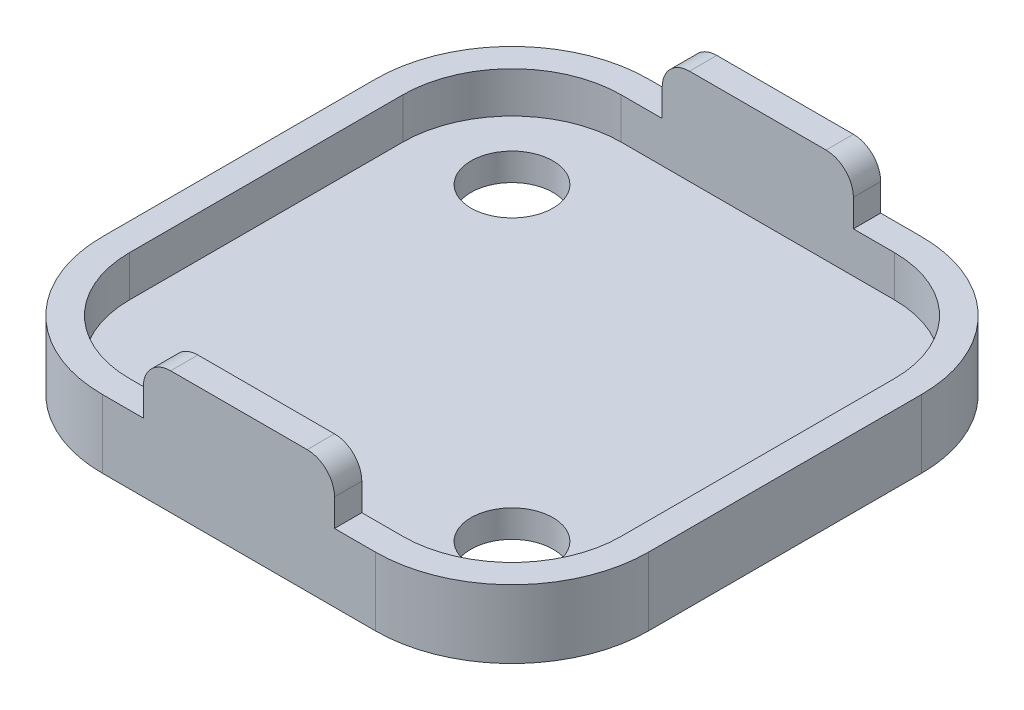
SolidWorks part; units mm, degrees
ref_plane "Front Plane" through (0, 0, 0) normal (0, 0, 1) x (1, 0, 0)
ref_plane "Top Plane" through (0, 0, 0) normal (0, 1, 0) x (1, 0, 0)
ref_plane "Right Plane" through (0, 0, 0) normal (1, 0, 0) x (0, 0, -1)
sketch "Sketch1" plane through (0, 0, 0) normal (0, 1, 0) x (1, 0, 0)
  line L1 (-10, -10) -> (10, -10)
  line L2 (-10, -10) -> (-10, 10)
  line L3 (-10, 10) -> (10, 10)
  line L4 (10, -10) -> (10, 10)
  line L5 (-10, -10) -> (10, 10) construction
  line L6 (-10, 10) -> (10, -10) construction
  point P0 (0, 0)
  dimension "D1" = 20
extrude "Boss-Extrude1" add sketch "Sketch1" along normal blind 2.5
fillet "Fillet1" radius 5 4 edges at (-10, 1.25, -10) (-10, 1.25, 10) (10, 1.25, -10) (10, 1.25, 10)
sketch "Sketch2" plane through (0, 2.5, 0) normal (0, 1, 0) x (1, 0, 0)
  circle A0 centre (-5.6569, 5.6569) radius 1.35 construction
  circle A1 centre (-5.6569, 5.6569) radius 1.35 construction
  circle A2 centre (5.6569, -5.6569) radius 1.35 construction
  circle A3 centre (5.6569, -5.6569) radius 1.35 construction
  circle A4 centre (5.6569, -5.6569) radius 1.5
  circle A5 centre (-5.6569, 5.6569) radius 1.5
  dimension "D1" = 3
extrude "Cut-Extrude1" cut sketch "Sketch2" against normal blind 10
sketch "Sketch3" plane through (0, 2.5, 0) normal (0, 1, 0) x (1, 0, 0)
  line L8 (5, 9) -> (-5, 9)
  line L9 (-9, 5) -> (-9, -5)
  line L10 (-5, -9) -> (5, -9)
  line L11 (9, -5) -> (9, 5)
  line L12 (5, 9) -> (-5, 9)
  line L13 (-9, 5) -> (-9, -5)
  line L14 (-5, -9) -> (5, -9)
  line L15 (9, -5) -> (9, 5)
  arc A8 (-5, 9) -> (-9, 5) centre (-5, 5) ccw
  arc A9 (-9, -5) -> (-5, -9) centre (-5, -5) ccw
  arc A10 (5, -9) -> (9, -5) centre (5, -5) ccw
  arc A11 (9, 5) -> (5, 9) centre (5, 5) ccw
  arc A12 (-5, 9) -> (-9, 5) centre (-5, 5) ccw
  arc A13 (-9, -5) -> (-5, -9) centre (-5, -5) ccw
  arc A14 (5, -9) -> (9, -5) centre (5, -5) ccw
  arc A15 (9, 5) -> (5, 9) centre (5, 5) ccw
  dimension "D1" = 1
extrude "Cut-Extrude2" cut sketch "Sketch3" against normal blind 1.5
sketch "Sketch4" plane through (0, 2.5, 0) normal (0, 1, 0) x (1, 0, 0)
  line L4 (3.5, -9) -> (3.5, 9)
  line L5 (3.5, 9) -> (-3.5, 9)
  line L6 (-3.5, 9) -> (-3.5, -9)
  line L7 (-3.5, -9) -> (3.5, -9)
  line L8 (3.5, -9) -> (3.5, 9)
  line L9 (3.5, 9) -> (-3.5, 9)
  line L10 (-3.5, 9) -> (-3.5, -9)
  line L11 (-3.5, -9) -> (3.5, -9)
  line L12 (3.5, -10) -> (3.5, 10)
  line L13 (-3.5, -10) -> (3.5, -10)
  line L14 (-3.5, 10) -> (-3.5, -10)
  line L15 (3.5, 10) -> (-3.5, 10)
  line L16 (3.5, -10) -> (3.5, 10)
  line L17 (-3.5, -10) -> (3.5, -10)
  line L18 (-3.5, 10) -> (-3.5, -10)
  line L19 (3.5, 10) -> (-3.5, 10)
  line M9 (-5, 9) -> (5, 9)
  line M13 (5, -9) -> (-5, -9)
  line M17 (5, 10) -> (-5, 10)
  line M21 (-5, -10) -> (5, -10)
  dimension "D1" = 0
  dimension "D2" = 0
extrude "Boss-Extrude2" add sketch "Sketch4" along normal blind 2 contours L18 L16 M17 M9 | L18 L16 M13 M21
fillet "Fillet2" radius 1 4 edges at (3.5, 4.5, 9.5) (-3.5, 4.5, 9.5) (3.5, 4.5, -9.5) (-3.5, 4.5, -9.5)
